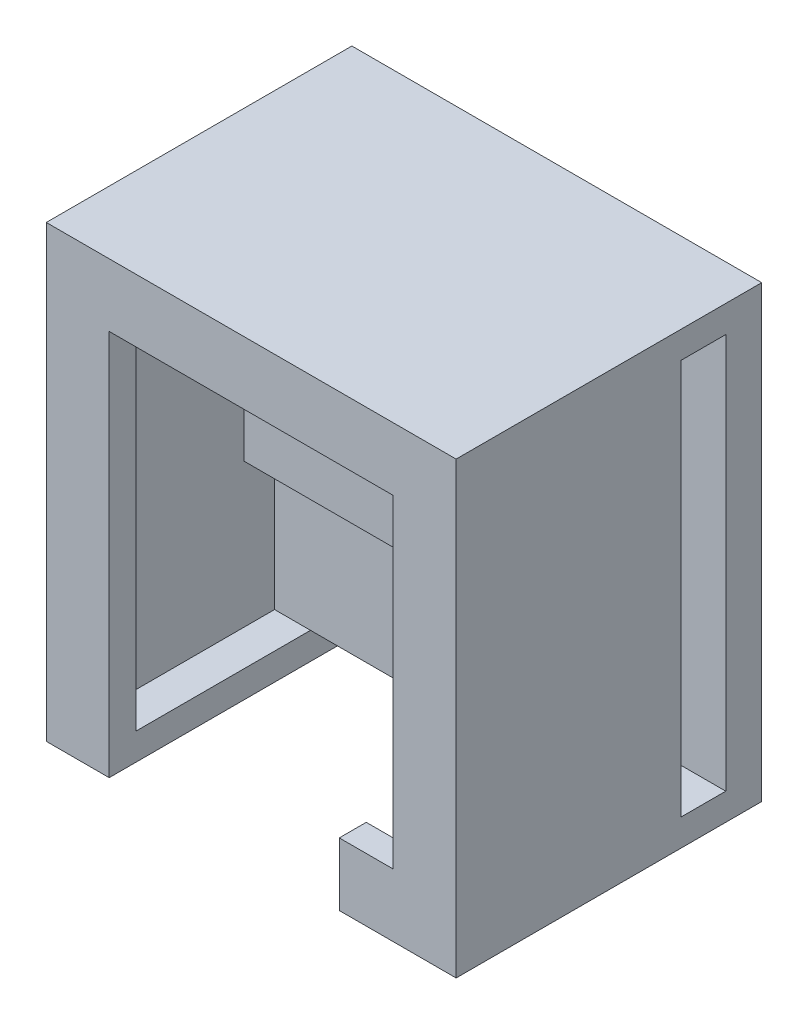
SolidWorks part; units mm, degrees
ref_plane "Alzado" through (0, 0, 0) normal (0, 0, 1) x (1, 0, 0)
ref_plane "Planta" through (0, 0, 0) normal (0, 1, 0) x (1, 0, 0)
ref_plane "Vista lateral" through (0, 0, 0) normal (1, 0, 0) x (0, 0, -1)
sketch "Croquis1" plane through (0, 0, 0) normal (0, 0, 1) x (1, 0, 0)
  line L0 (-55.6033, 22.6375) -> (-73.6033, 19.9375)
  line L2 (-75.3066, 17.9596) -> (-75.3066, -5.318)
  line L3 (-75.3066, -5.318) -> (-35.3066, -5.318)
  line L4 (-35.3066, 17.9596) -> (-35.3066, -5.318)
  line L5 (-55.0099, 22.6375) -> (-37.0099, 19.9375)
  line L6 (-55.3066, 22.682) -> (-35.3066, 22.682) construction
  circle A0 centre (-71.3066, 15.682) radius 1.5
  circle A1 centre (-39.3066, 15.682) radius 1.5
  arc A2 (-37.0099, 19.9375) -> (-35.3066, 17.9596) centre (-37.3066, 17.9596) cw
  arc A3 (-55.6033, 22.6375) -> (-55.0099, 22.6375) centre (-55.3066, 20.6596) cw
  arc A4 (-73.6033, 19.9375) -> (-75.3066, 17.9596) centre (-73.3066, 17.9596) ccw
  point P17 (-75.3066, 19.682)
  dimension "D3" = 2
  dimension "D4" = 32
  dimension "D5" = 3
  dimension "D6" = 3
  dimension "D1" = 7
  dimension "D2" = 3
  dimension "D7" = 4
extrude "Saliente-Extruir1" add sketch "Croquis1" along normal blind 3
sketch "Croquis2" plane through (0, 0, 3) normal (0, 0, 1) x (1, 0, 0)
  line L0 (-75.3066, -5.318) -> (-35.3066, -5.318) construction
  line L1 (-66.7066, -5.318) -> (-65.2066, -5.318)
  line L2 (-66.7066, -5.318) -> (-66.7066, 18.182)
  line L3 (-66.7066, 18.182) -> (-43.9066, 18.182)
  line L4 (-43.9066, -5.318) -> (-43.9066, 18.182)
  line L5 (-45.4066, -5.318) -> (-43.9066, -5.318)
  line L6 (-65.2066, 16.682) -> (-45.4066, 16.682)
  line L7 (-65.2066, 16.682) -> (-65.2066, -5.318)
  line L9 (-45.4066, 16.682) -> (-45.4066, -5.318)
  dimension "D1" = 22.8
  dimension "D3" = 23.5
  dimension "D4" = 1.5
  dimension "D5" = 1.5
  dimension "D6" = 1.5
extrude "Saliente-Extruir2" add sketch "Croquis2" along normal blind 8
sketch "Croquis3" plane through (0, -5.318, 0) normal (0, -1, 0) x (1, 0, 0)
  line L1 (-65.2066, 3) -> (-52.2066, 3)
  line L2 (-65.2066, 3) -> (-65.2066, 1.3)
  line L3 (-65.2066, 1.3) -> (-52.2066, 1.3)
  line L4 (-52.2066, 3) -> (-52.2066, 1.3)
  dimension "D1" = 13
  dimension "D2" = 1.7
extrude "Cortar-Extruir1" cut sketch "Croquis3" against normal blind 8
sketch "Croquis5" plane through (0, -5.318, 0) normal (0, -1, 0) x (1, 0, 0)
  line L0 (-75.3066, 0) -> (-35.3066, 0) construction
  line L1 (-66.7066, 11) -> (-63.2066, 11)
  line L2 (-66.7066, 11) -> (-66.7066, 0)
  line L3 (-66.7066, 0) -> (-63.2066, 0)
  line L4 (-63.2066, 11) -> (-63.2066, 0)
  line L5 (-45.4066, 11) -> (-45.4066, 3) construction
  line L6 (-43.9066, 11) -> (-50.4066, 11)
  line L7 (-43.9066, 11) -> (-43.9066, 0)
  line L8 (-43.9066, 0) -> (-50.4066, 0)
  line L9 (-50.4066, 11) -> (-50.4066, 0)
  line L10 (-65.2066, 11) -> (-65.2066, 1.3) construction
  dimension "D1" = 5
  dimension "D2" = 2
extrude "Saliente-Extruir3" add sketch "Croquis5" along normal blind 1.5
sketch "Croquis6" plane through (0, 0, 11) normal (0, 0, 1) x (1, 0, 0)
  line L0 (-63.2066, -5.318) -> (-63.2066, -6.818)
  line L1 (-63.2066, -6.818) -> (-66.7066, -6.818)
  line L2 (-66.7066, -6.818) -> (-66.7066, 18.182)
  line L3 (-66.7066, 18.182) -> (-43.9066, 18.182)
  line L4 (-43.9066, 18.182) -> (-43.9066, -6.818)
  line L5 (-43.9066, -6.818) -> (-50.4066, -6.818)
  line L6 (-50.4066, -6.818) -> (-50.4066, -3.318)
  line L7 (-50.4066, -3.318) -> (-47.4066, -3.318)
  line L8 (-47.4066, -3.318) -> (-47.4066, 14.682)
  line L9 (-47.4066, 14.682) -> (-63.2066, 14.682)
  line L10 (-63.2066, 14.682) -> (-63.2066, -5.318)
  dimension "D1" = 15.8
extrude "Saliente-Extruir4" add sketch "Croquis6" along normal blind 1.5
sketch "Croquis7" plane through (0, 0, 12.5) normal (0, 0, 1) x (1, 0, 0)
  line L0 (-66.7066, -6.818) -> (-66.7066, 18.182)
  line L1 (-66.7066, 18.182) -> (-43.9066, 18.182)
  line L2 (-43.9066, 18.182) -> (-43.9066, -6.818)
  line L3 (-43.9066, -6.818) -> (-20.5363, -6.818)
  line L4 (-20.5363, -6.818) -> (-20.5363, 28.4198)
  line L5 (-20.5363, 28.4198) -> (-79.7167, 28.4198)
  line L6 (-79.7167, 28.4198) -> (-79.7167, -6.818)
  line L7 (-79.7167, -6.818) -> (-66.7066, -6.818)
extrude "Cortar-Extruir2" cut sketch "Croquis7" against normal up to vertex
sketch "Croquis11" plane through (0, 0, 0) normal (0, 0, -1) x (-1, 0, 0)
  line L16 (66.7066, 18.182) -> (43.9066, 18.182)
  line L17 (43.9066, 18.182) -> (43.9066, -6.818)
  line L18 (43.9066, -6.818) -> (50.4066, -6.818)
  line L19 (50.4066, -6.818) -> (50.4066, -5.318)
  line L20 (50.4066, -5.318) -> (63.2066, -5.318)
  line L21 (63.2066, -5.318) -> (63.2066, -6.818)
  line L22 (63.2066, -6.818) -> (66.7066, -6.818)
  line L23 (66.7066, -6.818) -> (66.7066, 18.182)
  line L24 (66.7066, 18.182) -> (43.9066, 18.182)
  line L25 (43.9066, 18.182) -> (43.9066, -6.818)
  line L26 (43.9066, -6.818) -> (50.4066, -6.818)
  line L27 (50.4066, -6.818) -> (50.4066, -5.318)
  line L28 (50.4066, -5.318) -> (63.2066, -5.318)
  line L29 (63.2066, -5.318) -> (63.2066, -6.818)
  line L30 (63.2066, -6.818) -> (66.7066, -6.818)
  line L31 (66.7066, -6.818) -> (66.7066, 18.182)
  dimension "D1" = 0
extrude "Saliente-Extruir10" add sketch "Croquis11" along normal blind 4.5
sketch "Croquis12" plane through (-43.9066, 0, 0) normal (1, 0, 0) x (0, 0, -1)
  line L0 (4.5, 18.182) -> (4.5, -6.818) construction
  line L1 (0, -5.318) -> (2.5, -5.318)
  line L2 (0, -5.318) -> (0, 16.682)
  line L3 (0, 16.682) -> (2.5, 16.682)
  line L4 (2.5, -5.318) -> (2.5, 16.682)
  line L5 (-12.5, 18.182) -> (4.5, 18.182) construction
  dimension "D1" = 22
  dimension "D2" = 2
  dimension "D3" = 2.5
  dimension "D4" = 1.5
extrude "Cortar-Extruir3" cut sketch "Croquis12" against normal up to vertex
